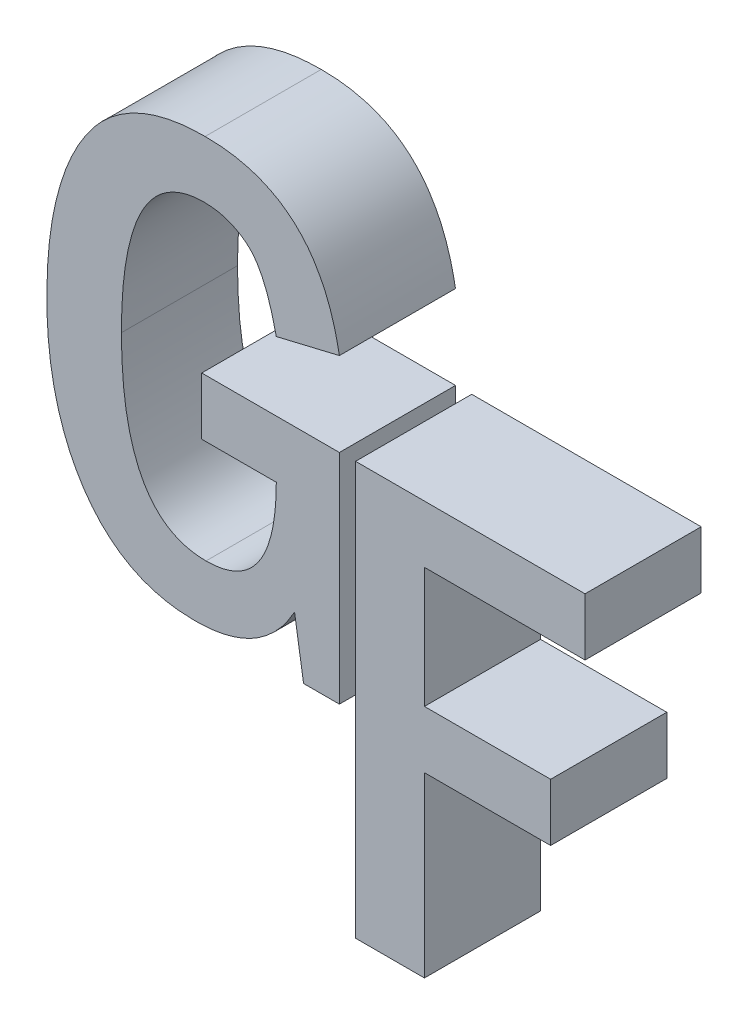
SolidWorks part; units mm, degrees
ref_plane "Front Plane" through (0, 0, 0) normal (0, 0, 1) x (1, 0, 0)
ref_plane "Top Plane" through (0, 0, 0) normal (0, 1, 0) x (1, 0, 0)
ref_plane "Right Plane" through (0, 0, 0) normal (1, 0, 0) x (0, 0, -1)
sketch "Sketch1" plane through (0, 0, 0) normal (0, 0, 1) x (1, 0, 0)
  text T0 "G" font "Franklin Gothic Medium Cond" height in points 72
  text T1 "F" font "Franklin Gothic Medium Cond" height in points 72
  point P3 (-0.9344, 13.6396)
  point P4 (0, 0)
  point P5 (-0.6367, 12.5083)
  point P6 (2.7428, 11.7799)
extrude "Boss-Extrude1" add sketch "Sketch1" against normal blind 5
